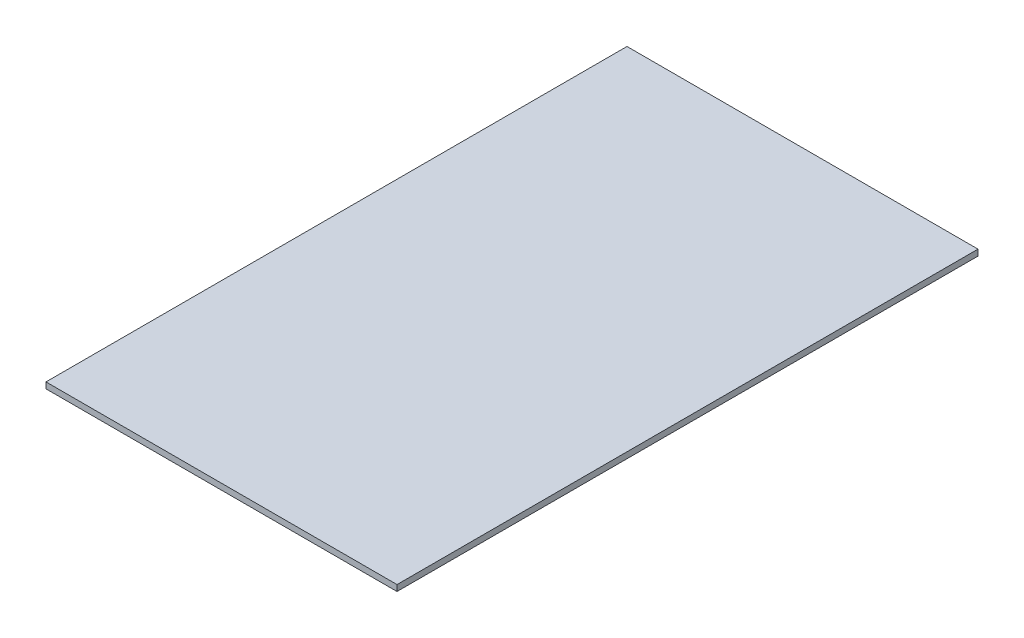
SolidWorks part; units mm, degrees
ref_plane "Front Plane" through (0, 0, 0) normal (0, 0, 1) x (1, 0, 0)
ref_plane "Top Plane" through (0, 0, 0) normal (0, 1, 0) x (1, 0, 0)
ref_plane "Right Plane" through (0, 0, 0) normal (1, 0, 0) x (0, 0, -1)
sketch "Sketch1" plane through (0, 0, 0) normal (0, 1, 0) x (1, 0, 0)
  line L1 (0, 0) -> (184.15, 0)
  line L2 (0, 0) -> (0, 304.8)
  line L3 (0, 304.8) -> (184.15, 304.8)
  line L4 (184.15, 0) -> (184.15, 304.8)
  dimension "D1" = 184.15
  dimension "D2" = 304.8
extrude "Boss-Extrude1" add sketch "Sketch1" along normal blind 3.175
